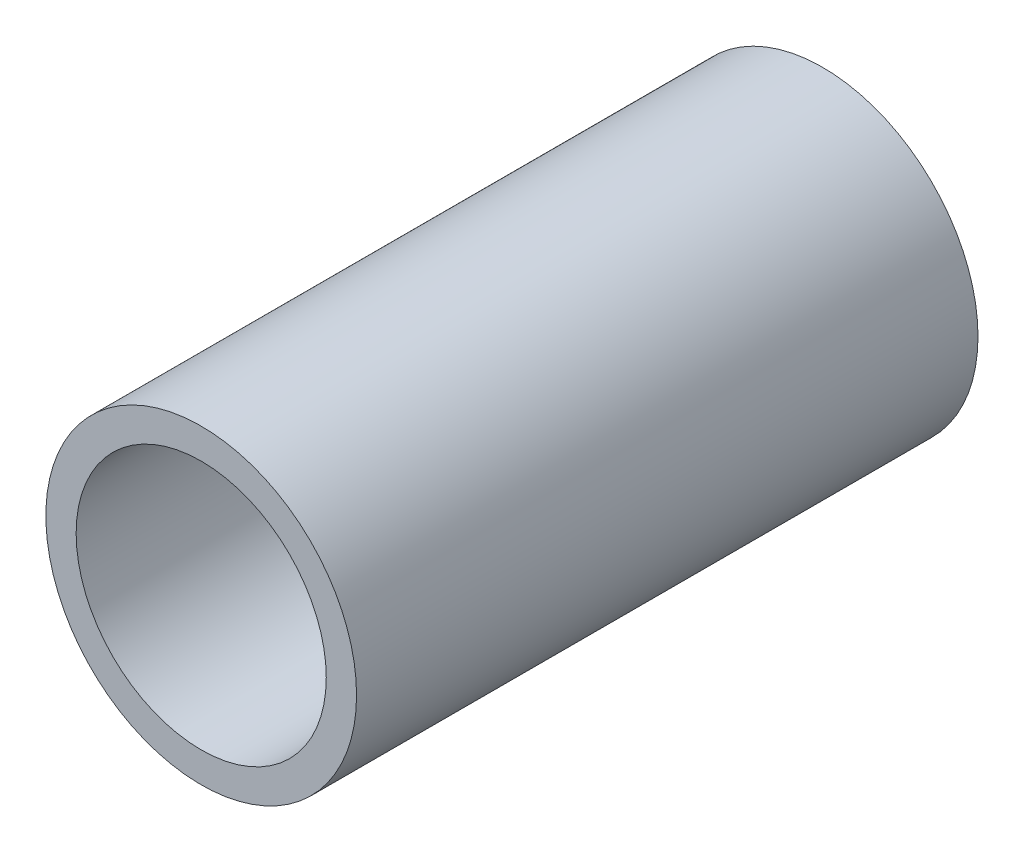
SolidWorks part; units mm, degrees
material "Brass"
ref_plane "Front Plane" through (0, 0, 0) normal (0, 0, 1) x (1, 0, 0)
ref_plane "Top Plane" through (0, 0, 0) normal (0, 1, 0) x (1, 0, 0)
ref_plane "Right Plane" through (0, 0, 0) normal (1, 0, 0) x (0, 0, -1)
sketch "Sketch1" plane through (0, 0, 0) normal (0, 0, 1) x (1, 0, 0)
  circle A0 centre (0, 0) radius 5
  circle A1 centre (0, 0) radius 4.025
  dimension "D1" = 10
  dimension "D2" = 8.05
extrude "Boss-Extrude1" add sketch "Sketch1" along normal blind 20
